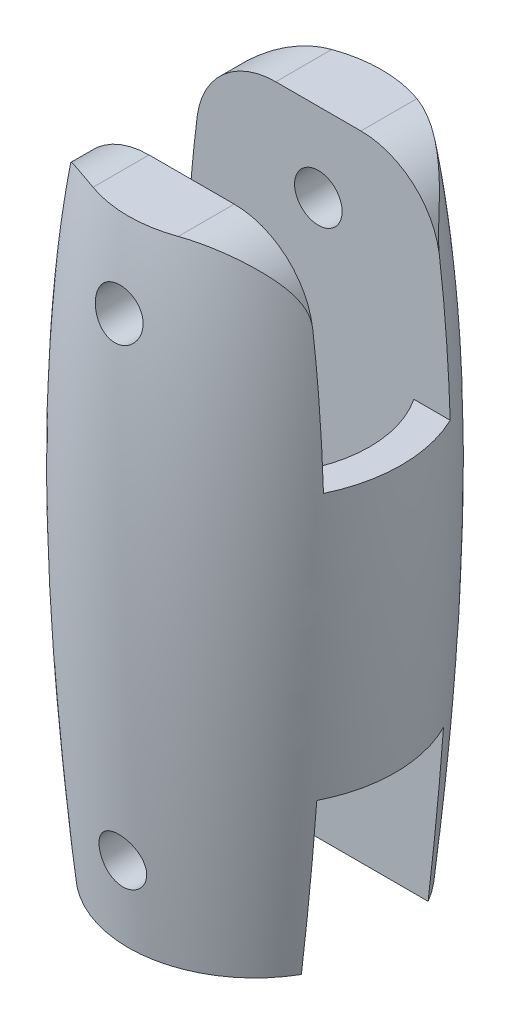
SolidWorks part; units mm, degrees
ref_plane "Front Plane" through (0, 0, 0) normal (0, 0, 1) x (1, 0, 0)
ref_plane "Top Plane" through (0, 0, 0) normal (0, 1, 0) x (1, 0, 0)
ref_plane "Right Plane" through (0, 0, 0) normal (1, 0, 0) x (0, 0, -1)
sketch "Sketch1" plane through (0, 0, 0) normal (1, 0, 0) x (0, 0, -1)
  line L0 (0, 20) -> (0, -20)
  line L1 (0, 20) -> (8, 20)
  line L2 (0, -20) -> (8, -20)
  line L3 (13.2094, -9.5442) -> (2.7906, 49.5442) construction
  spline S0 degree 2 poles (8, 20) (10.6047, 5.2279) (8, -20) knots 0 0 0 1 1 1
  point P3 (0, 0)
  dimension "D3" = 100
  dimension "D4" = 30
  dimension "D1" = 40
  dimension "D2" = 8
revolve "Revolve1" add sketch "Sketch1" angle 360 about L0
sketch "Sketch2" plane through (0, 0, 0) normal (1, 0, 0) x (0, 0, -1)
  line L0 (8, 20) -> (-8, 20) construction
  line L1 (-4, 7) -> (4, 7)
  line L2 (-4, 7) -> (-4, 20)
  line L3 (-4, 20) -> (4, 20)
  line L4 (4, 7) -> (4, 20)
  line L5 (-8, -20) -> (8, -20) construction
  line L6 (-4, -20) -> (4, -20)
  line L7 (-4, -20) -> (-4, -10)
  line L8 (-4, -10) -> (4, -10)
  line L9 (4, -20) -> (4, -10)
  point P12 (0, -10)
  point P14 (0, 7)
  dimension "D1" = 8
  dimension "D2" = 10
  dimension "D3" = 13
extrude "Cut-Extrude1" cut sketch "Sketch2" against normal through all and the other way through all
sketch "Sketch3" plane through (0, 0, 0) normal (0, 0, 1) x (1, 0, 0)
  line L0 (0, -20) -> (0, -15) construction
  line L1 (-6.9282, -20) -> (6.9282, -20) construction
  line L2 (0, 20) -> (0, 15) construction
  line L3 (6.9282, 20) -> (-6.9282, 20) construction
  circle A0 centre (0, 15) radius 1.5
  circle A1 centre (0, -15) radius 1.5
  dimension "D3" = 3
  dimension "D1" = 5
  dimension "D2" = 5
extrude "Cut-Extrude2" cut sketch "Sketch3" against normal through all and the other way through all
sketch "Sketch4" plane through (0, 7, 0) normal (0, 1, 0) x (1, 0, 0)
  line L0 (-8.3247, -4) -> (8.3247, -4) construction
  line L16 (-8.3247, -4) -> (8.3247, -4)
  line L17 (-8.3247, 4) -> (8.3247, 4) construction
  line L18 (-8.3247, 4) -> (8.3247, 4)
  line L21 (-6.954, 2) -> (6.954, 2) construction
  line L22 (-6.954, -2) -> (6.954, -2) construction
  arc A0 (8.3247, -4) -> (8.3247, 4) centre (0, 0) ccw construction
  arc A1 (-8.3247, 4) -> (-8.3247, -4) centre (0, 0) ccw construction
  arc A16 (8.3247, -4) -> (8.3247, 4) centre (0, 0) ccw
  arc A17 (-8.3247, 4) -> (-8.3247, -4) centre (0, 0) ccw
  arc A18 (6.954, -2) -> (6.954, 2) centre (0, 0) ccw
  arc A19 (-6.954, 2) -> (-6.954, -2) centre (0, 0) ccw
  circle A20 centre (0, 0) radius 7.2359
  dimension "D1" = 2
extrude "Cut-Extrude3" cut sketch "Sketch4" against normal through all
sketch "Sketch5" plane through (0, 0, 0) normal (0, 0, 1) x (1, 0, 0)
  line L0 (6.9282, 20) -> (-6.9282, 20) construction
  line L1 (6.9282, 20) -> (-6.9282, 20)
  arc A0 (-7.6463, 15.6441) -> (-2.6879, 20) centre (-2.6879, 15) cw
  arc A1 (2.6879, 20) -> (7.6463, 15.6441) centre (2.6879, 15) cw
  spline S0 degree 3 poles (998.7082, -131.3472) (-99.0882, -165.5063) (16.3553, -69.3336) (2.2304, 68.9408) (-57.7068, 118.5226) (-991.597, 74.2202) knots -18.611286 -18.611286 -18.611286 -18.611286 0.5 0.5 13.28032 13.28032 13.28032 13.28032 only from (8.3247, 7) to (6.9282, 20) construction
  spline S1 degree 3 poles (991.5997, 74.2201) (57.7069, 118.5227) (-2.2304, 68.9409) (-16.3553, -69.3335) (99.088, -165.5062) (-998.7055, -131.3473) knots -12.280332 -12.280332 -12.280332 -12.280332 0.5 0.5 19.61127 19.61127 19.61127 19.61127 only from (-6.9282, 20) to (-8.3247, 7) construction
  spline S2 degree 3 poles (8.3247, 7) (8.249, 9.1835) (8.1123, 11.3605) (7.6694, 15.6963) (7.3649, 17.8552) (6.9282, 20) knots 0 0 0 0 0.5 0.5 1 1 1 1
  spline S3 degree 3 poles (-6.9282, 20) (-7.3649, 17.8552) (-7.6694, 15.6963) (-8.1123, 11.3605) (-8.249, 9.1835) (-8.3247, 7) knots 0 0 0 0 0.5 0.5 1 1 1 1
  dimension "D1" = 5
extrude "Cut-Extrude4" cut sketch "Sketch5" against normal blind 20 from offset 10 contours A1 S2 L1 | L1 S3 A0
